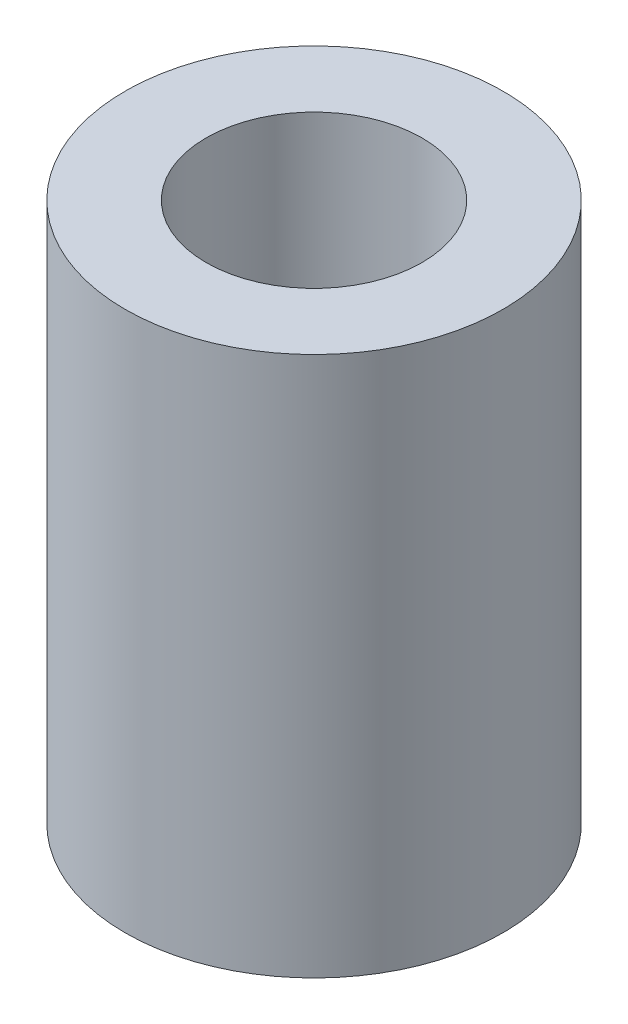
SolidWorks part; units mm, degrees
ref_plane "前视基准面" through (0, 0, 0) normal (0, 0, 1) x (1, 0, 0)
ref_plane "上视基准面" through (0, 0, 0) normal (0, 1, 0) x (1, 0, 0)
ref_plane "右视基准面" through (0, 0, 0) normal (1, 0, 0) x (0, 0, -1)
other "Configuration Table"
sketch "草图1" plane through (0, 0, 0) normal (0, 1, 0) x (1, 0, 0)
  circle A0 centre (0, 0) radius 1.75
  circle A1 centre (0, 0) radius 1
  dimension "D1" = 3.5
  dimension "D2" = 2
extrude "凸台-拉伸1" add sketch "草图1" along normal blind 5
